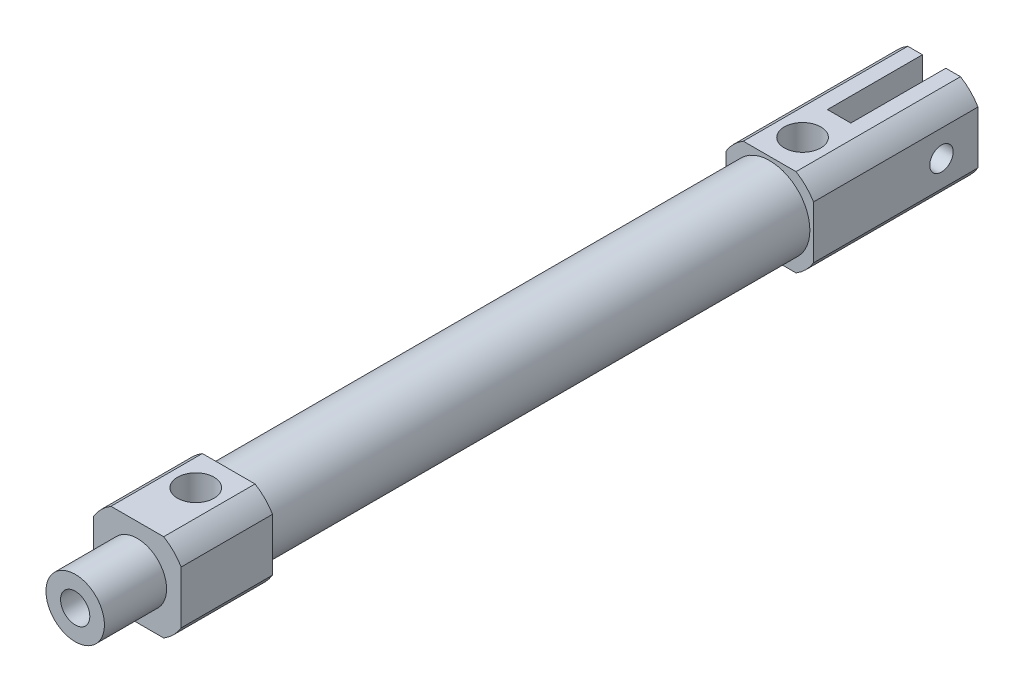
SolidWorks part; units mm, degrees
material "6061 合金"
ref_plane "前视基准面" through (0, 0, 0) normal (0, 0, 1) x (1, 0, 0)
ref_plane "上视基准面" through (0, 0, 0) normal (0, 1, 0) x (1, 0, 0)
ref_plane "右视基准面" through (0, 0, 0) normal (1, 0, 0) x (0, 0, -1)
sketch "草图1" plane through (0, 0, 0) normal (0, 0, 1) x (1, 0, 0)
  circle A0 centre (0, 0) radius 7
  dimension "D1" = 14
extrude "凸台-拉伸1" add sketch "草图1" along normal blind 22.5
sketch "草图2" plane through (0, 0, 22.5) normal (0, 0, 1) x (1, 0, 0)
  circle A0 centre (0, 0) radius 5.5
  circle A1 centre (0, 0) radius 5
  dimension "D1" = 11
  dimension "D2" = 10
extrude "凸台-拉伸2" add sketch "草图2" along normal blind 74
sketch "草图3" plane through (0, 0, 96.5) normal (0, 0, 1) x (1, 0, 0)
  circle A0 centre (0, 0) radius 7
  dimension "D1" = 14
extrude "凸台-拉伸3" add sketch "草图3" along normal blind 12.5
sketch "草图4" plane through (0, 0, 109) normal (0, 0, 1) x (1, 0, 0)
  circle A0 centre (0, 0) radius 4
  dimension "D1" = 8
extrude "凸台-拉伸4" add sketch "草图4" along normal blind 8.5
sketch "草图5" plane through (0, 0, 117.5) normal (0, 0, 1) x (1, 0, 0)
  circle A0 centre (0, 0) radius 2
  dimension "D1" = 4
extrude "切除-拉伸1" cut sketch "草图5" against normal blind 50
sketch "草图6" plane through (0, 0, 109) normal (0, 0, 1) x (1, 0, 0)
  line L1 (-6, 6) -> (6, 6)
  line L2 (-6, 6) -> (-6, -6)
  line L3 (-6, -6) -> (6, -6)
  line L4 (6, 6) -> (6, -6)
  line L5 (-6, 6) -> (6, -6) construction
  line L6 (-6, -6) -> (6, 6) construction
  circle A0 centre (0, 0) radius 10
  point P0 (0, 0)
  dimension "D3" = 20
  dimension "D1" = 12
  dimension "D2" = 12
extrude "切除-拉伸2" cut sketch "草图6" against normal through all
sketch "草图7" plane through (0, 0, 0) normal (0, 0, -1) x (-1, 0, 0)
  line L0 (3.6056, -6) -> (-3.6056, -6) construction
  line L1 (-1.6, 6) -> (1.6, 6)
  line L2 (-1.6, 6) -> (-1.6, -6)
  line L3 (-1.6, -6) -> (1.6, -6)
  line L4 (1.6, 6) -> (1.6, -6)
  line L5 (-1.6, 6) -> (1.6, -6) construction
  line L6 (-1.6, -6) -> (1.6, 6) construction
  point P0 (0, 0)
  dimension "D1" = 3.2
extrude "切除-拉伸3" cut sketch "草图7" against normal blind 13
sketch "草图8" plane through (6, 0, 0) normal (1, 0, 0) x (0, 0, -1)
  line L0 (0, 0) -> (-22.5, 0) construction
  line L1 (-22.5, 5.5) -> (-22.5, -5.5) construction
  line L2 (0, -3.6056) -> (0, 3.6056) construction
  circle A0 centre (-5, 0) radius 1.6
  dimension "D1" = 3.2
  dimension "D2" = 5
extrude "切除-拉伸4" cut sketch "草图8" against normal through all
sketch "草图9" plane through (0, 6, 0) normal (0, 1, 0) x (1, 0, 0)
  line L0 (0, 0) -> (0, -18) construction
  circle A0 centre (0, -18) radius 2.5
  dimension "D2" = 5
  dimension "D1" = 18
extrude "切除-拉伸5" cut sketch "草图9" against normal blind 5
sketch "草图10" plane through (0, 6, 0) normal (0, 1, 0) x (1, 0, 0)
  line L0 (0, -109) -> (0, -96.5) construction
  line L1 (3.6056, -109) -> (-3.6056, -109) construction
  line L2 (5.5, -96.5) -> (-5.5, -96.5) construction
  circle A0 centre (0, -101) radius 2.5
  dimension "D1" = 8
  dimension "D2" = 5
extrude "切除-拉伸6" cut sketch "草图10" against normal blind 5
